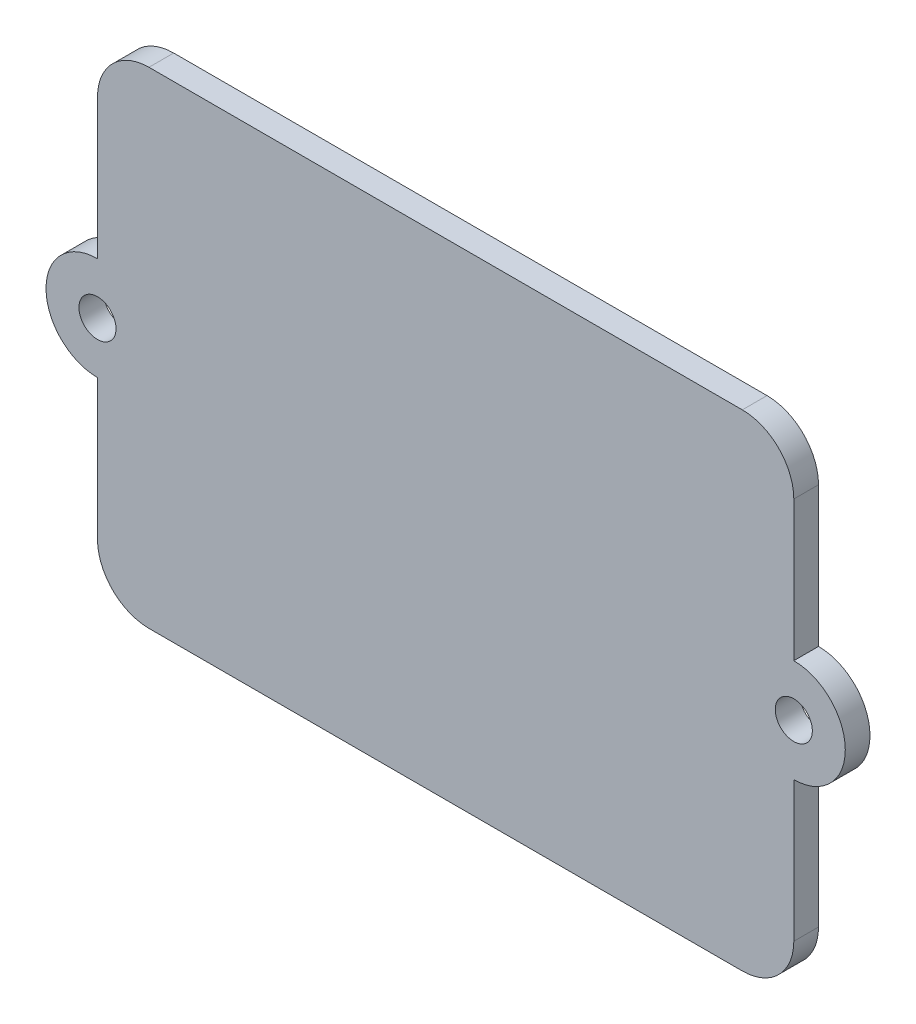
SolidWorks part; units mm, degrees
material "PET"
ref_plane "Front Plane" through (0, 0, 0) normal (0, 0, 1) x (1, 0, 0)
ref_plane "Top Plane" through (0, 0, 0) normal (0, 1, 0) x (1, 0, 0)
ref_plane "Right Plane" through (0, 0, 0) normal (1, 0, 0) x (0, 0, -1)
sketch "Sketch1" plane through (0, 0, 0) normal (0, 0, 1) x (1, 0, 0)
  line L1 (0, 0) -> (42.945, 0)
  line L2 (0, 0) -> (0, 29.972)
  line L3 (0, 29.972) -> (42.945, 29.972)
  line L4 (42.945, 0) -> (42.945, 29.972)
  dimension "D1" = 29.972
  dimension "D2" = 42.945
extrude "Boss-Extrude1" add sketch "Sketch1" along normal blind 1.524
sketch "Sketch2" plane through (0, 0, 1.524) normal (0, 0, 1) x (1, 0, 0)
  line L0 (0, 29.972) -> (0, 0) construction
  line L1 (42.945, 0) -> (42.945, 29.972) construction
  circle A0 centre (0, 14.986) radius 3.175
  circle A1 centre (42.945, 14.986) radius 3.175
  dimension "D1" = 6.35
  dimension "D2" = 6.35
extrude "Boss-Extrude2" add sketch "Sketch2" against normal up to surface (1.524 mm away) up to face at (21.4725, 14.986, 0)
sketch "Sketch3" plane through (0, 0, 1.524) normal (0, 0, 1) x (1, 0, 0)
  line L0 (42.945, 11.811) -> (42.945, 18.161) construction
  line L1 (0, 11.811) -> (0, 18.161) construction
  circle A0 centre (0, 14.986) radius 1.143
  circle A1 centre (42.945, 14.986) radius 1.143
  point P12 (0, 14.986)
  point P13 (42.926, 13.0745)
  point P14 (42.926, 14.986)
  point P15 (42.926, 14.986)
  point P16 (42.926, 14.9484)
  point P17 (0, 0)
  dimension "D1" = 2.286
  dimension "D2" = 2.286
extrude "Cut-Extrude1" cut sketch "Sketch3" against normal through all
fillet "Fillet1" radius 3.175 4 edges at (0, 29.972, 0.762) (42.945, 29.972, 0.762) (42.945, 0, 0.762) (0, 0, 0.762)
